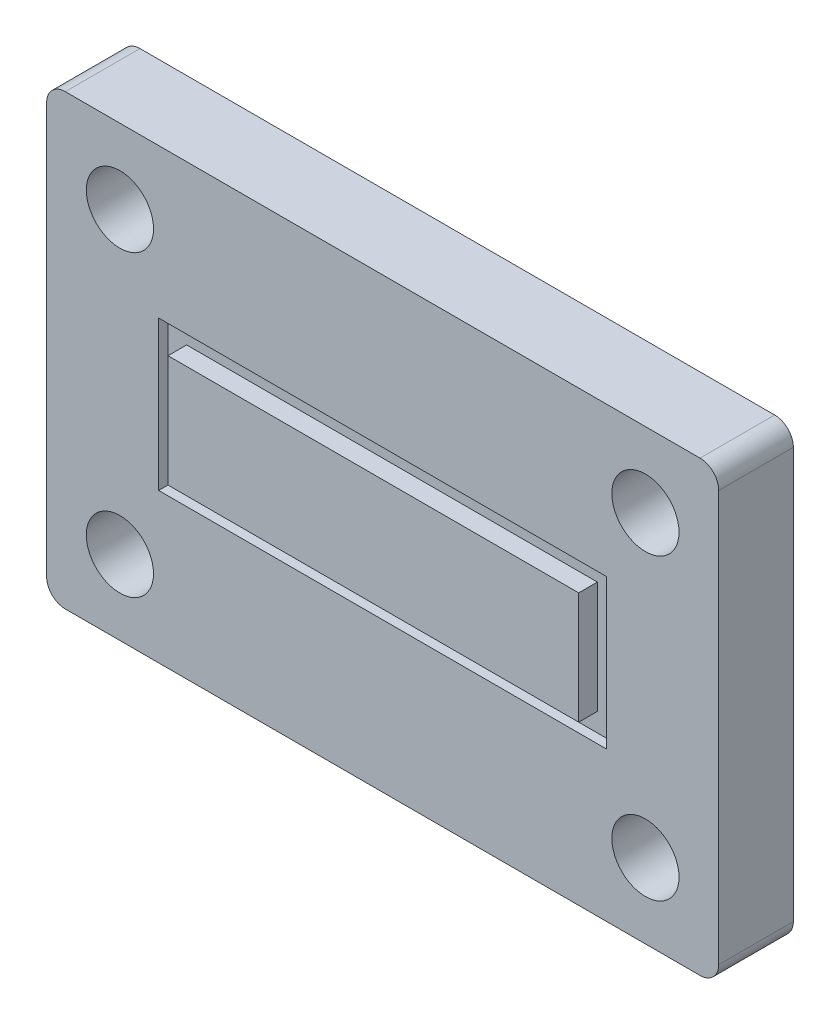
SolidWorks part; units mm, degrees
ref_plane "Płaszczyzna przednia" through (0, 0, 0) normal (0, 0, 1) x (1, 0, 0)
ref_plane "Płaszczyzna górna" through (0, 0, 0) normal (0, 1, 0) x (1, 0, 0)
ref_plane "Płaszczyzna prawa" through (0, 0, 0) normal (1, 0, 0) x (0, 0, -1)
sketch "Sketch1" plane through (0, 0, 0) normal (0, 0, 1) x (1, 0, 0)
  line L1 (0, 0) -> (36, 0)
  line L2 (0, 0) -> (0, 24)
  line L3 (0, 24) -> (36, 24)
  line L4 (36, 0) -> (36, 24)
  dimension "D1" = 36
  dimension "D2" = 24
extrude "Boss-Extrude1" add sketch "Sketch1" along normal blind 4
hole_wizard "M3 Clearance Hole1" positions "Sketch2" profile "Sketch3" hole size "M3" standard "DIN"
sketch "Sketch2" plane through (0, 0, 4) normal (0, 0, 1) x (1, 0, 0)
  line L0 (3.925, 20) -> (32.075, 4)
  line L2 (32.075, 20) -> (3.925, 4)
  line L4 (18, 24) -> (18, 12)
  line L5 (36, 24) -> (0, 24) construction
  line L7 (0, 12) -> (18, 12)
  line L8 (0, 24) -> (0, 0) construction
  line L11 (18, 12) -> (36, 12)
  line L12 (36, 0) -> (36, 24) construction
  line L14 (18, 12) -> (18, 0)
  line L15 (0, 0) -> (36, 0) construction
  point P0 (3.925, 20)
  point P6 (32.075, 20)
  point P7 (32.075, 4)
  point P8 (3.925, 4)
  dimension "D3" = 16
  dimension "D1" = 2
  dimension "D2" = 2
sketch "Sketch3" plane through (3.925, 20, 4) normal (1, 0, 0) x (0, -1, 0)
  line L0 (0, 0) -> (0, 17.0815)
  line L1 (0, 17.0815) -> (1.8, 16)
  line L2 (1.8, 16) -> (1.8, 0)
  line L5 (1.8, 0) -> (0, 0)
  line L10 (0, 17.0815) -> (-1.8, 16) construction
  line L11 (0, -6.35) -> (0, 107.95) construction
  dimension "Hole Dia." = 3.6
  dimension "Hole Depth" = 16
  dimension "Drill Angle" = 118
fillet "Fillet1" radius 1 4 edges at (36, 24, 2) (36, 0, 2) (0, 0, 2) (0, 24, 2)
sketch "Sketch4" plane through (0, 0, 4) normal (0, 0, 1) x (1, 0, 0)
  line L0 (18, 24) -> (18, 16) construction
  line L1 (6, 16) -> (30, 16)
  line L2 (6, 16) -> (6, 8)
  line L3 (6, 8) -> (30, 8)
  line L4 (30, 16) -> (30, 8)
  line L5 (35, 24) -> (1, 24) construction
  line L6 (6, 12) -> (0, 12) construction
  line L7 (0, 23) -> (0, 1) construction
  line L8 (30, 11.086) -> (36, 11.086) construction
  line L9 (36, 1) -> (36, 23) construction
  line L10 (23.7948, 0) -> (23.7948, 8) construction
  line L11 (1, 0) -> (35, 0) construction
  dimension "D1" = 8
  dimension "D2" = 24
extrude "Cut-Extrude1" cut sketch "Sketch4" against normal blind 0.5
sketch "Sketch5" plane through (0, 0, 3.5) normal (0, 0, 1) x (1, 0, 0)
  line L0 (7, 15) -> (7, 9)
  line L1 (7, 9) -> (29, 9)
  line L2 (29, 9) -> (29, 15)
  line L3 (29, 15) -> (7, 15)
  line L4 (6, 16) -> (6, 8)
  line L5 (6, 8) -> (30, 8)
  line L6 (30, 8) -> (30, 16)
  line L7 (30, 16) -> (6, 16)
  line L8 (6, 16) -> (6, 8)
  line L9 (6, 8) -> (30, 8)
  line L10 (30, 8) -> (30, 16)
  line L11 (30, 16) -> (6, 16)
  dimension "D1" = 0
  dimension "D2" = 1
extrude "Boss-Extrude2" add sketch "Sketch5" along normal blind 1 separate body contours L0 L1 L2 L3
